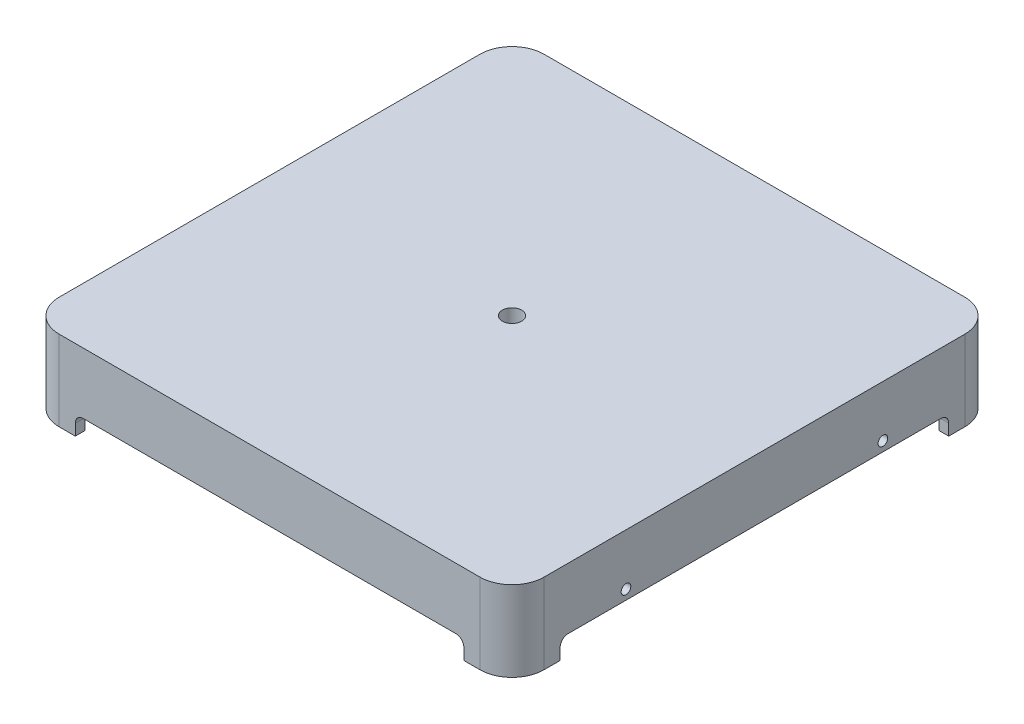
SolidWorks part; units mm, degrees
ref_plane "Front Plane" through (0, 0, 0) normal (0, 0, 1) x (1, 0, 0)
ref_plane "Top Plane" through (0, 0, 0) normal (0, 1, 0) x (1, 0, 0)
ref_plane "Right Plane" through (0, 0, 0) normal (1, 0, 0) x (0, 0, -1)
sketch "Sketch1" plane through (0, 0, 0) normal (0, 1, 0) x (1, 0, 0)
  line L5 (-75.5, 75.5) -> (75.5, 75.5)
  line L11 (-75.5, 75.5) -> (-75.5, -75.5)
  line L12 (-75.5, -75.5) -> (75.5, -75.5)
  line L13 (75.5, 75.5) -> (75.5, -75.5)
  line L14 (-75.5, 75.5) -> (75.5, -75.5) construction
  line L15 (-75.5, -75.5) -> (75.5, 75.5) construction
  point P0 (0, 0)
  dimension "D1" = 151
extrude "Boss-Extrude1" add sketch "Sketch1" along normal blind 25
sketch "Sketch2" plane through (0, 0, 0) normal (0, -1, 0) x (1, 0, 0)
  line L0 (-75.5, 75.5) -> (75.5, 75.5) construction
  line L1 (-72.5, 72.5) -> (72.5, 72.5)
  line L2 (-72.5, 72.5) -> (-72.5, -72.5)
  line L3 (-72.5, -72.5) -> (72.5, -72.5)
  line L4 (72.5, 72.5) -> (72.5, -72.5)
  line L5 (-72.5, 72.5) -> (72.5, -72.5) construction
  line L6 (-72.5, -72.5) -> (72.5, 72.5) construction
  point P0 (0, 0)
  dimension "D1" = 3
extrude "Cut-Extrude1" cut sketch "Sketch2" against normal blind 12
sketch "Sketch3" plane through (0, 0, 75.5) normal (0, 0, 1) x (1, 0, 0)
  line L0 (-75.5, 0) -> (75.5, 0) construction
  line L1 (-60.5, 0) -> (60.5, 0)
  line L2 (-60.5, 0) -> (-60.5, 6)
  line L3 (-60.5, 6) -> (60.5, 6)
  line L4 (60.5, 0) -> (60.5, 6)
  line L5 (-75.5, 0) -> (-60.5, 0) construction
  line L6 (60.5, 0) -> (75.5, 0) construction
  dimension "D1" = 15
  dimension "D2" = 6
extrude "Cut-Extrude2" cut sketch "Sketch3" against normal through all
sketch "Sketch4" plane through (-75.5, 0, 0) normal (-1, 0, 0) x (0, 0, 1)
  line L0 (-75.5, 0) -> (75.5, 0) construction
  line L1 (-60.5, 0) -> (60.5, 0)
  line L2 (-60.5, 0) -> (-60.5, 6)
  line L3 (-60.5, 6) -> (60.5, 6)
  line L4 (60.5, 0) -> (60.5, 6)
  line L5 (75.5, 6) -> (75.5, 0) construction
  line L6 (60.5, 0) -> (75.5, 0) construction
  line L7 (-60.5, 0) -> (-75.5, 0) construction
  dimension "D1" = 15
extrude "Cut-Extrude3" cut sketch "Sketch4" against normal through all
fillet "Fillet1" radius 10 8 edges at (-72.5, 6, 72.5) (72.5, 6, -72.5) (72.5, 6, 72.5) (-72.5, 6, -72.5) (75.5, 12.5, 75.5) (-75.5, 12.5, 75.5) (-75.5, 12.5, -75.5) (75.5, 12.5, -75.5)
sketch "Sketch5" plane through (0, 25, 0) normal (0, 1, 0) x (1, 0, 0)
  circle A0 centre (0, 0) radius 3
  dimension "D1" = 6
extrude "Cut-Extrude4" cut sketch "Sketch5" against normal through all
fillet "Fillet4" radius 2.5 8 edges at (74, 6, -60.5) (-74, 6, -60.5) (-60.5, 6, 74) (-60.5, 6, -74) (60.5, 6, -74) (-74, 6, 60.5) (74, 6, 60.5) (60.5, 6, 74)
sketch "Sketch6" plane through (-75.5, 0, 0) normal (1, 0, 0) x (0, 0, -1)
  line L0 (-40, 9) -> (40, 9) construction
  line L2 (-58, 6) -> (58, 6) construction
  circle A0 centre (-40, 9) radius 1.5
  circle A1 centre (40, 9) radius 1.5
  point P4 (0, 9)
  point P9 (0, 0)
  point P10 (0, 0)
  dimension "D2" = 3
  dimension "D1" = 80
  dimension "D3" = 3
extrude "Cut-Extrude5" cut sketch "Sketch6" along normal through all
